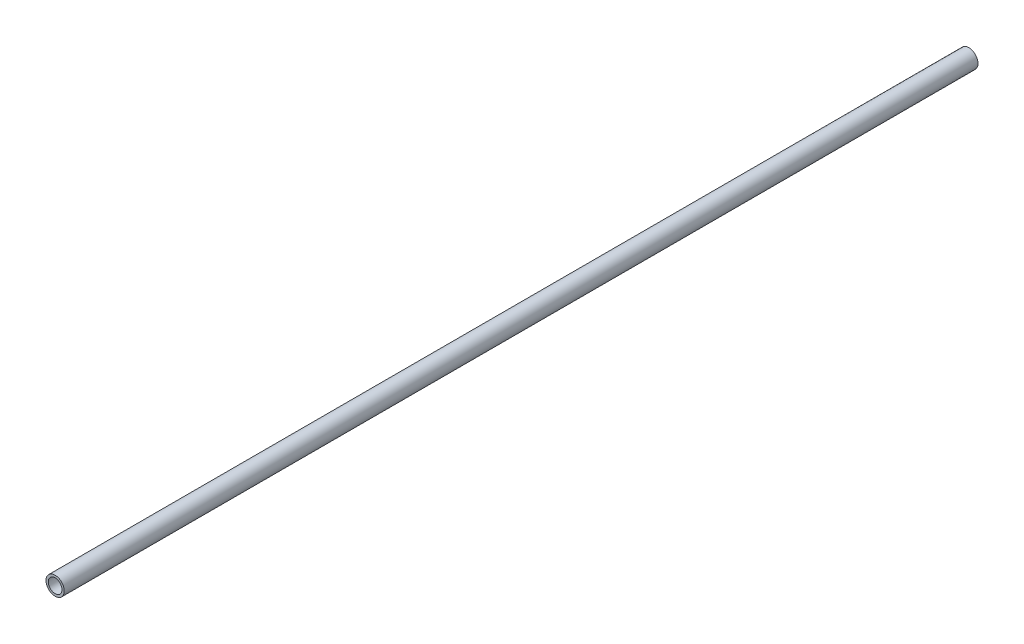
SolidWorks part; units mm, degrees
ref_plane "前视基准面" through (0, 0, 0) normal (0, 0, 1) x (1, 0, 0)
ref_plane "上视基准面" through (0, 0, 0) normal (0, 1, 0) x (1, 0, 0)
ref_plane "右视基准面" through (0, 0, 0) normal (1, 0, 0) x (0, 0, -1)
sketch "草图1" plane through (0, 0, 0) normal (0, 0, 1) x (1, 0, 0)
  circle A0 centre (0, 0) radius 3
  circle A1 centre (0, 0) radius 4
  dimension "D1" = 6
  dimension "D2" = 8
extrude "凸台-拉伸1" add sketch "草图1" along normal blind 400
